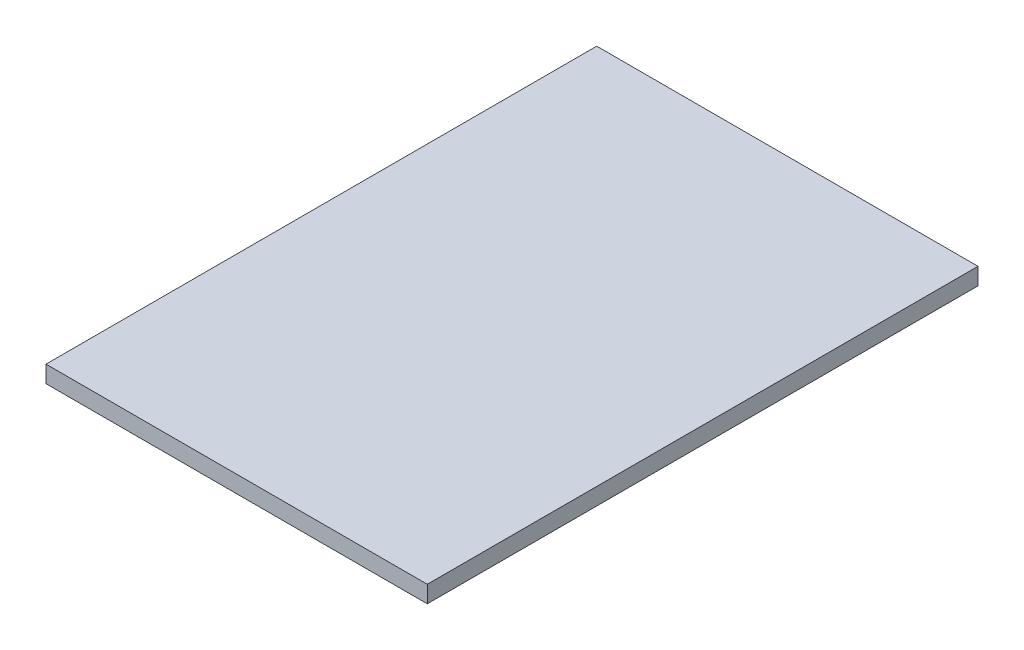
SolidWorks part; units mm, degrees
ref_plane "Front Plane" through (0, 0, 0) normal (0, 0, 1) x (1, 0, 0)
ref_plane "Top Plane" through (0, 0, 0) normal (0, 1, 0) x (1, 0, 0)
ref_plane "Right Plane" through (0, 0, 0) normal (1, 0, 0) x (0, 0, -1)
sketch "Sketch1" plane through (0, 0, 0) normal (0, 1, 0) x (1, 0, 0)
  line L1 (-225, -325) -> (225, -325)
  line L2 (-225, -325) -> (-225, 325)
  line L3 (-225, 325) -> (225, 325)
  line L4 (225, -325) -> (225, 325)
  line L5 (-225, -325) -> (225, 325) construction
  line L6 (-225, 325) -> (225, -325) construction
  point P0 (0, 0)
  dimension "D1" = 650
  dimension "D2" = 450
extrude "Boss-Extrude1" add sketch "Sketch1" along normal mid plane 20
